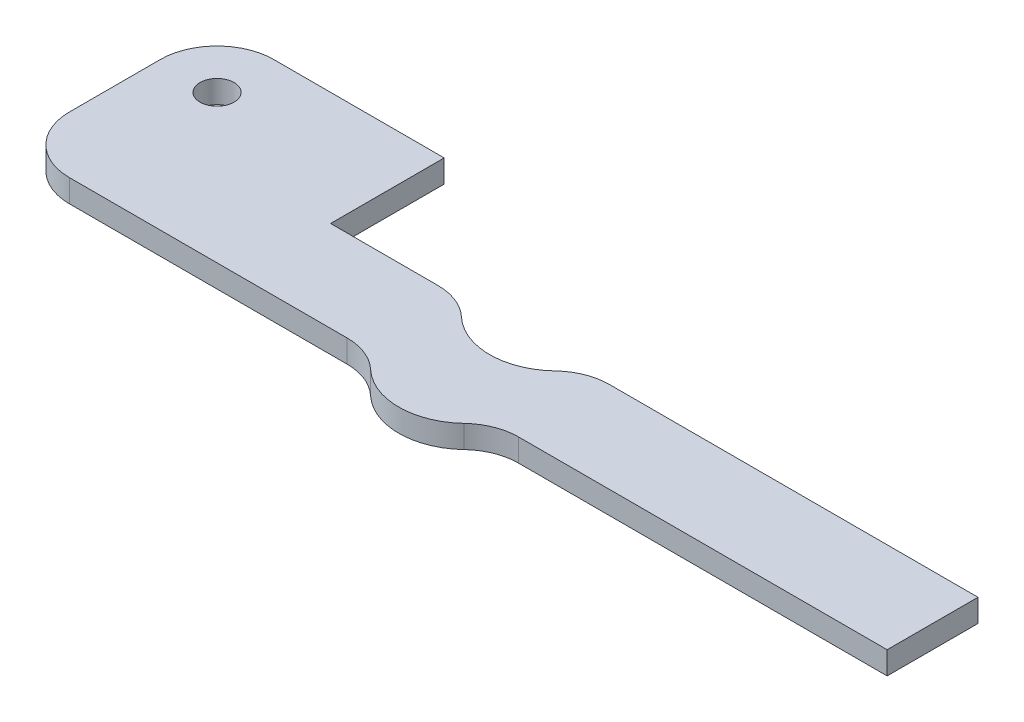
SolidWorks part; units mm, degrees
ref_plane "前视基准面" through (0, 0, 0) normal (0, 0, 1) x (1, 0, 0)
ref_plane "上视基准面" through (0, 0, 0) normal (0, 1, 0) x (1, 0, 0)
ref_plane "右视基准面" through (0, 0, 0) normal (1, 0, 0) x (0, 0, -1)
sketch "草图1" plane through (0, 0, 0) normal (0, 1, 0) x (1, 0, 0)
  line L0 (0, 73.2303) -> (0, -63.1712) construction
  line L1 (-67.7984, 0) -> (122.52, 0) construction
  line L2 (17.1962, -13) -> (52, -13)
  line L3 (-15, 5) -> (-25, 5)
  line L4 (-25, -13) -> (6.8038, -13)
  line L6 (-25, 5) -> (-25, -13)
  line L8 (-15, -5) -> (52, -5)
  line L10 (52, -13) -> (52, -5)
  line L11 (-15, 5) -> (-15, -5)
  circle A0 centre (-20, 0) radius 1.5
  arc A1 (6.8038, -13) -> (17.1962, -13) centre (12, -10) ccw
  dimension "D7" = 3
  dimension "D8" = 40
  dimension "D3" = 25
  dimension "D4" = 12
  dimension "D1" = 10
  dimension "D2" = 18
  dimension "D5" = 10
  dimension "D6" = 67
  dimension "D9" = 5
  dimension "D10" = 3
  dimension "D11" = 5
extrude "凸台-拉伸1" add sketch "草图1" along normal blind 2
fillet "圆角2" radius 5 1 edges at (-25, 1, -5)
fillet "圆角3" radius 5 1 edges at (-25, 1, 13)
sketch "草图7" plane through (0, 2, 0) normal (0, 1, 0) x (1, 0, 0)
  line L0 (52, -13) -> (52, -5) construction
  line L1 (52, -5) -> (-15, -5) construction
  circle A0 centre (12, -2) radius 6
  dimension "D3" = 12
  dimension "D1" = 40
  dimension "D2" = 3
extrude "切除-拉伸4" cut sketch "草图7" against normal blind 10
fillet "圆角5" radius 5 4 edges at (6.8038, 1, 5) (17.1962, 1, 5) (17.1962, 1, 13) (6.8038, 1, 13)
sketch "草图8" plane through (0, 0, 13) normal (0, 0, 1) x (1, 0, 0)
  line L0 (19.5498, 2) -> (52, 2) construction
  line L1 (52, 0) -> (42, 0)
  line L2 (52, 0) -> (52, 2)
  line L3 (52, 2) -> (42, 2)
  line L4 (42, 0) -> (42, 2)
  dimension "D1" = 10
extrude "凸台-拉伸3" [suppressed] add sketch "草图8" along normal blind 12
sketch "草图9" [suppressed] plane through (0, 2, 0) normal (0, 1, 0) x (1, 0, 0)
  line L0 (19.5498, -13) -> (42, -13) construction
  line L1 (47, -25) -> (47, -19) construction
  line L2 (52, -25) -> (42, -25) construction
  circle A0 centre (47, -19) radius 1.5
  dimension "D1" = 3
  dimension "D2" = 6
extrude "切除-拉伸5" [suppressed] cut sketch "草图9" against normal blind 12
fillet "圆角6" [suppressed] radius 2
sketch "草图10" plane through (-15, 0, 0) normal (1, 0, 0) x (0, 0, -1)
  line L1 (5, 0) -> (-5, 0)
  line L2 (5, 0) -> (5, 2)
  line L3 (5, 2) -> (-5, 2)
  line L4 (-5, 0) -> (-5, 2)
  dimension "D1" = 10
  dimension "D2" = 2
extrude "凸台-拉伸4" add sketch "草图10" along normal blind 10
fillet "圆角8" [suppressed] radius 5
sketch "草图13" [suppressed] plane through (0, 0, 13) normal (0, 0, 1) x (1, 0, 0)
  line L0 (48.5, 9) -> (48.5, 5) construction
  line L1 (45, 9) -> (52, 9) construction
  circle A0 centre (48.5, 5) radius 1.25
  dimension "D1" = 2.5
  dimension "D2" = 4
extrude "切除-拉伸7" [suppressed] cut sketch "草图13" against normal blind 9
cosmetic thread "装饰螺纹线2" parameters "D2"=3
